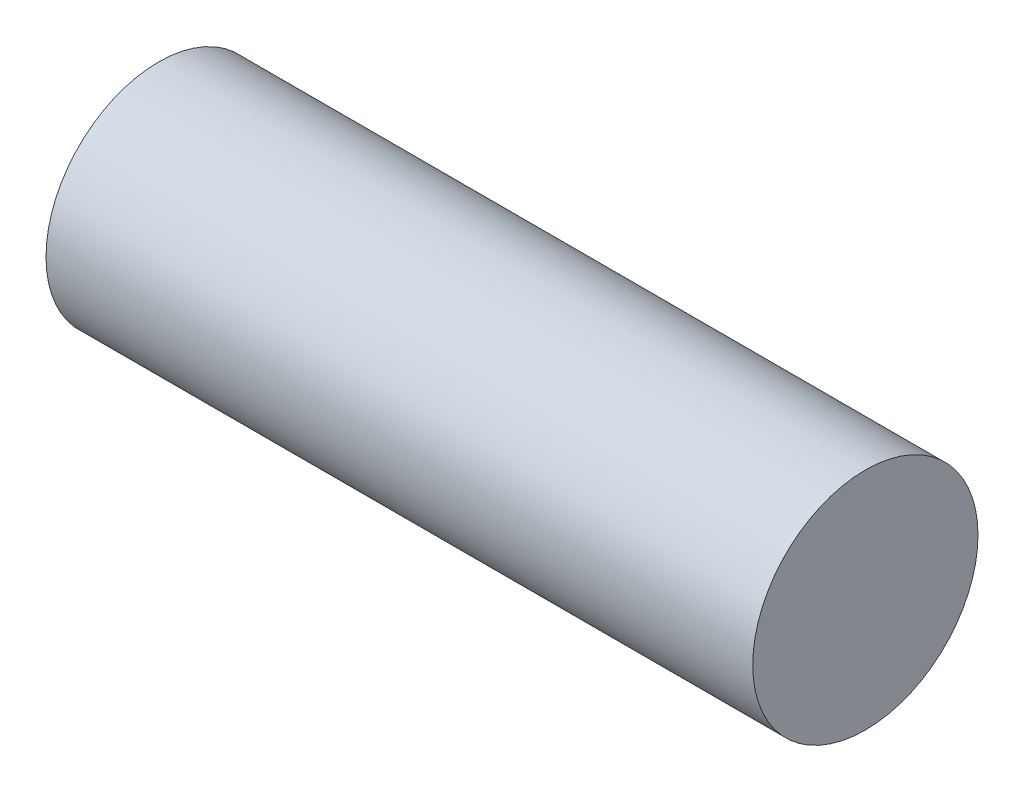
SolidWorks part; units mm, degrees
ref_plane "Front Plane" through (0, 0, 0) normal (0, 0, 1) x (1, 0, 0)
ref_plane "Top Plane" through (0, 0, 0) normal (0, 1, 0) x (1, 0, 0)
ref_plane "Right Plane" through (0, 0, 0) normal (1, 0, 0) x (0, 0, -1)
sketch "Sketch2" plane through (0, 0, 0) normal (0, 1, 0) x (1, 0, 0)
  line L0 (0, 0) -> (400, 0)
  line L1 (400, 0) -> (400, 63.75)
  line L2 (400, 63.75) -> (0, 63.75)
  line L3 (0, 63.75) -> (0, 0)
revolve "Revolve1" add sketch "Sketch2" angle 360 about L2
